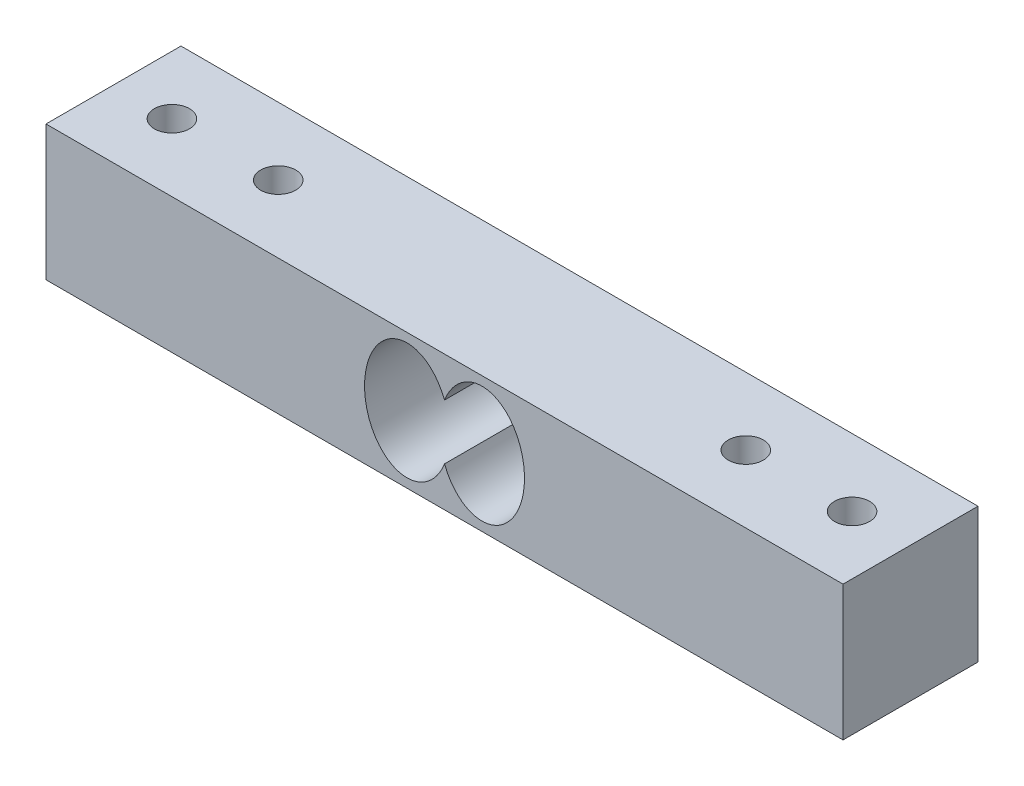
SolidWorks part; units mm, degrees
ref_plane "Front Plane" through (0, 0, 0) normal (0, 0, 1) x (1, 0, 0)
ref_plane "Top Plane" through (0, 0, 0) normal (0, 1, 0) x (1, 0, 0)
ref_plane "Right Plane" through (0, 0, 0) normal (1, 0, 0) x (0, 0, -1)
sketch "Sketch1" plane through (0, 0, 0) normal (0, 1, 0) x (1, 0, 0)
  line L0 (-32, 0) -> (32, 0) construction
  line L1 (-37.5, -6.35) -> (37.5, -6.35)
  line L2 (-37.5, -6.35) -> (-37.5, 6.35)
  line L3 (-37.5, 6.35) -> (37.5, 6.35)
  line L4 (37.5, -6.35) -> (37.5, 6.35)
  line L5 (-37.5, -6.35) -> (37.5, 6.35) construction
  line L6 (-37.5, 6.35) -> (37.5, -6.35) construction
  circle A0 centre (-32, 0) radius 1.65
  circle A1 centre (-22, 0) radius 1.65
  circle A2 centre (22, 0) radius 1.65
  circle A3 centre (32, 0) radius 1.65
  point P0 (0, 0)
  point P5 (-20.5747, 0.1822)
  point P12 (-28.059, 0.495)
  point P14 (21.4475, -0.19)
  point P17 (0, 0)
  point P18 (28.2596, -0.292)
  dimension "D3" = 64
  dimension "D6" = 3.3
  dimension "D1" = 75
  dimension "D2" = 12.7
  dimension "D4" = 44
  dimension "D5" = 10
extrude "Boss-Extrude1" add sketch "Sketch1" along normal mid plane 12.7
sketch "Sketch2" plane through (0, 0, 0) normal (0, 0, 1) x (1, 0, 0)
  line L0 (-3.5248, 5.5) -> (3.5248, 5.5) construction
  line L1 (0, 2.6) -> (0, -2.6) construction
  ellipse E0 centre (-3.5248, 0) end of major axis (-3.5248, -5.5) minor radius 4 (0, -2.6) -> (0, 2.6) cw
  ellipse E1 centre (3.5248, 0) end of major axis (3.5248, 5.5) minor radius 4 (0, -2.6) -> (0, 2.6) ccw
  point P1 (0, 5.5)
  point P2 (0, 0)
  point P7 (0, 0)
  dimension "D1" = 5.5
  dimension "D2" = 4
  dimension "D3" = 5.2
extrude "Cut-Extrude1" cut sketch "Sketch2" against normal through all both and the other way through all
